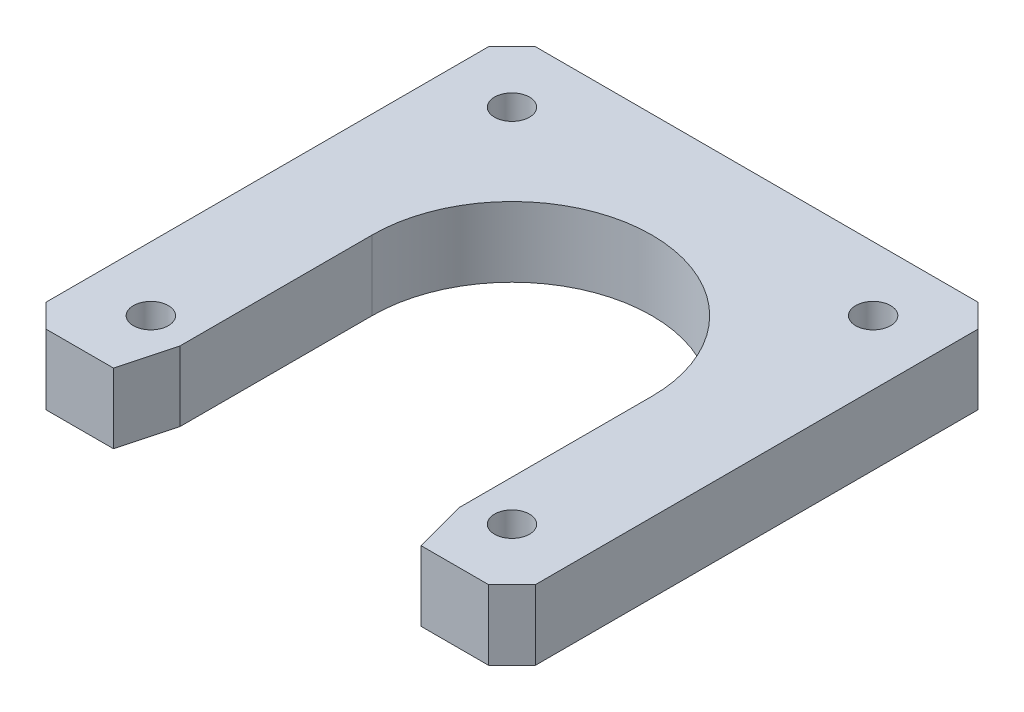
SolidWorks part; units mm, degrees
ref_plane "Front Plane" through (0, 0, 0) normal (0, 0, 1) x (1, 0, 0)
ref_plane "Top Plane" through (0, 0, 0) normal (0, 1, 0) x (1, 0, 0)
ref_plane "Right Plane" through (0, 0, 0) normal (1, 0, 0) x (0, 0, -1)
sketch "Sketch1" plane through (0, 0, 0) normal (0, 1, 0) x (1, 0, 0)
  line L1 (-21, -21) -> (21, -21)
  line L2 (-21, -21) -> (-21, 21)
  line L3 (-21, 21) -> (21, 21)
  line L4 (21, -21) -> (21, 21)
  line L5 (-21, -21) -> (21, 21) construction
  line L6 (-21, 21) -> (21, -21) construction
  line L7 (-15.5, 15.5) -> (15.5, 15.5) construction
  line L8 (-15.5, 15.5) -> (-15.5, -15.5) construction
  line L9 (-15.5, -15.5) -> (15.5, -15.5) construction
  line L10 (15.5, 15.5) -> (15.5, -15.5) construction
  circle A0 centre (0, 0) radius 12
  circle A1 centre (-15.5, 15.5) radius 1.5
  circle A2 centre (15.5, 15.5) radius 1.5
  circle A3 centre (15.5, -15.5) radius 1.5
  circle A4 centre (-15.5, -15.5) radius 1.5
  point P0 (0, 0)
  dimension "D2" = 24
  dimension "D3" = 3
  dimension "D1" = 42
  dimension "D4" = 31
extrude "Boss-Extrude1" add sketch "Sketch1" along normal blind 6
chamfer "Chamfer1" distance 2 angle 45 4 edges at (-21, 3, -21) (21, 3, -21) (21, 3, 21) (-21, 3, 21)
sketch "Sketch2" plane through (0, 6, 0) normal (0, 1, 0) x (1, 0, 0)
  line L0 (-12, 0) -> (-12, -21)
  line L1 (-19, -21) -> (19, -21) construction
  line L2 (-12, -21) -> (12, -21)
  line L3 (12, -21) -> (12, 0)
  line L4 (12, 0) -> (-12, 0)
  circle A0 centre (0, 0) radius 12 construction
extrude "Cut-Extrude1" cut sketch "Sketch2" against normal through all
chamfer "Chamfer2" distance 4.5 angle 15 2 edges at (12, 3, 21) (-12, 3, 21)
equation "\"M3_d\"= \"M3_d_laser@troublemaker.Assembly\""
equation "\"housing_t\"= \"housing_t_glob@troublemaker.Assembly\""
equation "\"D3@Sketch1\"=\"M3_d\""
equation "\"D1@Boss-Extrude1\"=\"housing_t\""
